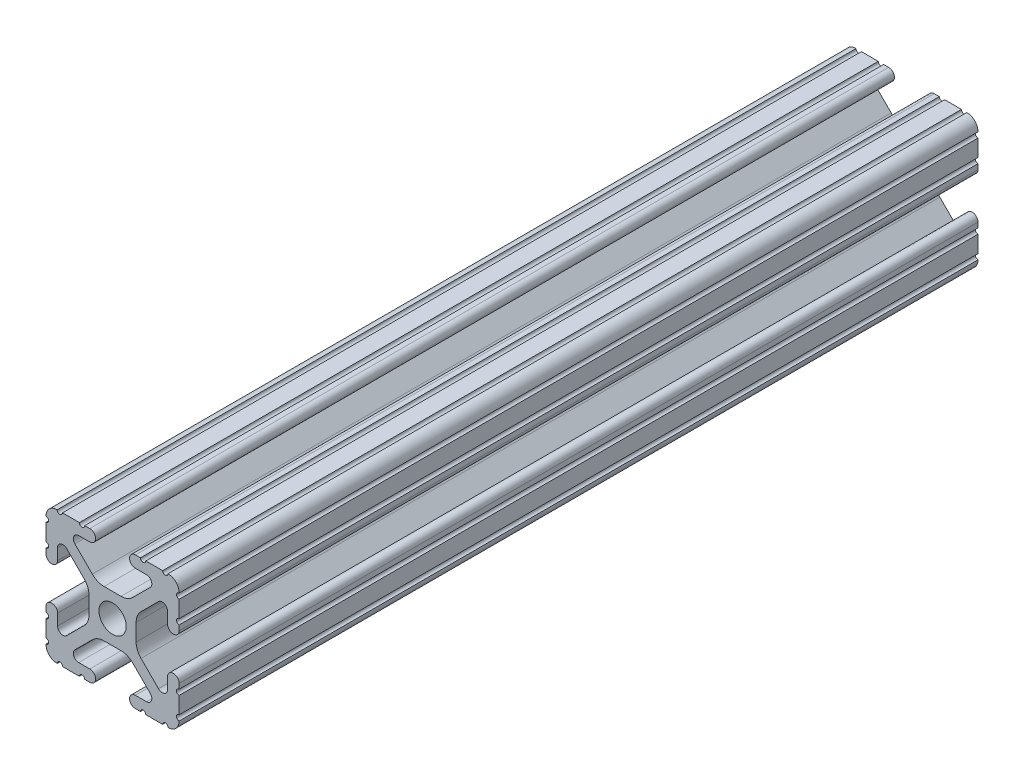
SolidWorks part; units mm, degrees
ref_plane "Front Plane" through (0, 0, 0) normal (0, 0, 1) x (1, 0, 0)
ref_plane "Top Plane" through (0, 0, 0) normal (0, 1, 0) x (1, 0, 0)
ref_plane "Right Plane" through (0, 0, 0) normal (1, 0, 0) x (0, 0, -1)
ref_plane "Plane1" through (0, 0, -2463.8) normal (0, 0, -1) x (-1, 0, 0)
sketch "Sketch1" plane through (0, 0, -2463.8) normal (0, 0, -1) x (-1, 0, 0)
  line L0 (12.7, -9.5504) -> (12.7, -6.3331)
  line L1 (12.7, -5.3171) -> (12.7, -4.3434)
  line L2 (10.4902, -4.3434) -> (10.4902, -6.4748)
  line L3 (8.7558, -7.1932) -> (5.4257, -3.8632)
  line L4 (4.4958, -1.6181) -> (4.4958, 1.6181)
  line L5 (5.4257, 3.8632) -> (8.7558, 7.1932)
  line L6 (10.4902, 6.4748) -> (10.4902, 4.3434)
  line L7 (12.7, 4.3434) -> (12.7, 5.3171)
  line L8 (12.7, 6.3331) -> (12.7, 9.5504)
  line L9 (9.5504, 12.7) -> (6.3331, 12.7)
  line L10 (5.3171, 12.7) -> (4.3434, 12.7)
  line L11 (4.3434, 10.4902) -> (6.4748, 10.4902)
  line L12 (7.1932, 8.7558) -> (3.8632, 5.4257)
  line L13 (1.6181, 4.4958) -> (-1.6181, 4.4958)
  line L14 (-3.8632, 5.4257) -> (-7.1932, 8.7558)
  line L15 (-6.4748, 10.4902) -> (-4.3434, 10.4902)
  line L16 (-4.3434, 12.7) -> (-5.3171, 12.7)
  line L17 (-6.3331, 12.7) -> (-9.5504, 12.7)
  line L18 (-12.7, 9.5504) -> (-12.7, 6.3331)
  line L19 (-12.7, 5.3171) -> (-12.7, 4.3434)
  line L20 (-10.4902, 4.3434) -> (-10.4902, 6.4748)
  line L21 (-8.7558, 7.1932) -> (-5.4257, 3.8632)
  line L22 (-4.4958, 1.6181) -> (-4.4958, -1.6181)
  line L23 (-5.4257, -3.8632) -> (-8.7558, -7.1932)
  line L24 (-10.4902, -6.4748) -> (-10.4902, -4.3434)
  line L25 (-12.7, -4.3434) -> (-12.7, -5.3171)
  line L26 (-12.7, -6.3331) -> (-12.7, -9.5504)
  line L27 (-9.5504, -12.7) -> (-6.3331, -12.7)
  line L28 (-5.3171, -12.7) -> (-4.3434, -12.7)
  line L29 (-4.3434, -10.4902) -> (-6.4748, -10.4902)
  line L30 (-7.1932, -8.7558) -> (-3.8632, -5.4257)
  line L31 (-1.6181, -4.4958) -> (1.6181, -4.4958)
  line L32 (3.8632, -5.4257) -> (7.1932, -8.7558)
  line L33 (6.4748, -10.4902) -> (4.3434, -10.4902)
  line L34 (4.3434, -12.7) -> (5.3171, -12.7)
  line L35 (6.3331, -12.7) -> (9.5504, -12.7)
  arc A0 (12.6998, -10.5664) -> (12.7, -9.5504) centre (12.7, -10.0584) cw
  arc A1 (12.7, -6.3331) -> (12.7, -5.3171) centre (12.7, -5.8251) cw
  arc A2 (12.7, -4.3434) -> (10.4902, -4.3434) centre (11.5951, -4.3434) ccw
  arc A3 (10.4902, -6.4748) -> (8.7558, -7.1932) centre (9.4742, -6.4748) cw
  arc A4 (5.4257, -3.8632) -> (4.4958, -1.6181) centre (7.6708, -1.6181) cw
  arc A5 (4.4958, 1.6181) -> (5.4257, 3.8632) centre (7.6708, 1.6181) cw
  arc A6 (8.7558, 7.1932) -> (10.4902, 6.4748) centre (9.4742, 6.4748) cw
  arc A7 (10.4902, 4.3434) -> (12.7, 4.3434) centre (11.5951, 4.3434) ccw
  arc A8 (12.7, 5.3171) -> (12.7, 6.3331) centre (12.7, 5.8251) cw
  arc A9 (12.7, 9.5504) -> (12.6998, 10.5664) centre (12.7, 10.0584) cw
  arc A10 (12.6998, 10.5664) -> (10.5664, 12.6998) centre (10.5918, 10.5918) ccw
  arc A11 (10.5664, 12.6998) -> (9.5504, 12.7) centre (10.0584, 12.7) cw
  arc A12 (6.3331, 12.7) -> (5.3171, 12.7) centre (5.8251, 12.7) cw
  arc A13 (4.3434, 12.7) -> (4.3434, 10.4902) centre (4.3434, 11.5951) ccw
  arc A14 (6.4748, 10.4902) -> (7.1932, 8.7558) centre (6.4748, 9.4742) cw
  arc A15 (3.8632, 5.4257) -> (1.6181, 4.4958) centre (1.6181, 7.6708) cw
  arc A16 (-1.6181, 4.4958) -> (-3.8632, 5.4257) centre (-1.6181, 7.6708) cw
  arc A17 (-7.1932, 8.7558) -> (-6.4748, 10.4902) centre (-6.4748, 9.4742) cw
  arc A18 (-4.3434, 10.4902) -> (-4.3434, 12.7) centre (-4.3434, 11.5951) ccw
  arc A19 (-5.3171, 12.7) -> (-6.3331, 12.7) centre (-5.8251, 12.7) cw
  arc A20 (-9.5504, 12.7) -> (-10.5664, 12.6998) centre (-10.0584, 12.7) cw
  arc A21 (-10.5664, 12.6998) -> (-12.6998, 10.5664) centre (-10.5918, 10.5918) ccw
  arc A22 (-12.6998, 10.5664) -> (-12.7, 9.5504) centre (-12.7, 10.0584) cw
  arc A23 (-12.7, 6.3331) -> (-12.7, 5.3171) centre (-12.7, 5.8251) cw
  arc A24 (-12.7, 4.3434) -> (-10.4902, 4.3434) centre (-11.5951, 4.3434) ccw
  arc A25 (-10.4902, 6.4748) -> (-8.7558, 7.1932) centre (-9.4742, 6.4748) cw
  arc A26 (-5.4257, 3.8632) -> (-4.4958, 1.6181) centre (-7.6708, 1.6181) cw
  arc A27 (-4.4958, -1.6181) -> (-5.4257, -3.8632) centre (-7.6708, -1.6181) cw
  arc A28 (-8.7558, -7.1932) -> (-10.4902, -6.4748) centre (-9.4742, -6.4748) cw
  arc A29 (-10.4902, -4.3434) -> (-12.7, -4.3434) centre (-11.5951, -4.3434) ccw
  arc A30 (-12.7, -5.3171) -> (-12.7, -6.3331) centre (-12.7, -5.8251) cw
  arc A31 (-12.7, -9.5504) -> (-12.6998, -10.5664) centre (-12.7, -10.0584) cw
  arc A32 (-12.6998, -10.5664) -> (-10.5664, -12.6998) centre (-10.5918, -10.5918) ccw
  arc A33 (-10.5664, -12.6998) -> (-9.5504, -12.7) centre (-10.0584, -12.7) cw
  arc A34 (-6.3331, -12.7) -> (-5.3171, -12.7) centre (-5.8251, -12.7) cw
  arc A35 (-4.3434, -12.7) -> (-4.3434, -10.4902) centre (-4.3434, -11.5951) ccw
  arc A36 (-6.4748, -10.4902) -> (-7.1932, -8.7558) centre (-6.4748, -9.4742) cw
  arc A37 (-3.8632, -5.4257) -> (-1.6181, -4.4958) centre (-1.6181, -7.6708) cw
  arc A38 (1.6181, -4.4958) -> (3.8632, -5.4257) centre (1.6181, -7.6708) cw
  arc A39 (7.1932, -8.7558) -> (6.4748, -10.4902) centre (6.4748, -9.4742) cw
  arc A40 (4.3434, -10.4902) -> (4.3434, -12.7) centre (4.3434, -11.5951) ccw
  arc A41 (5.3171, -12.7) -> (6.3331, -12.7) centre (5.8251, -12.7) cw
  arc A42 (9.5504, -12.7) -> (10.5664, -12.6998) centre (10.0584, -12.7) cw
  arc A43 (10.5664, -12.6998) -> (12.6998, -10.5664) centre (10.5918, -10.5918) ccw
  circle A44 centre (0, 0) radius 2.6035
extrude "Boss-Extrude1" add sketch "Sketch1" along normal blind 152.4
